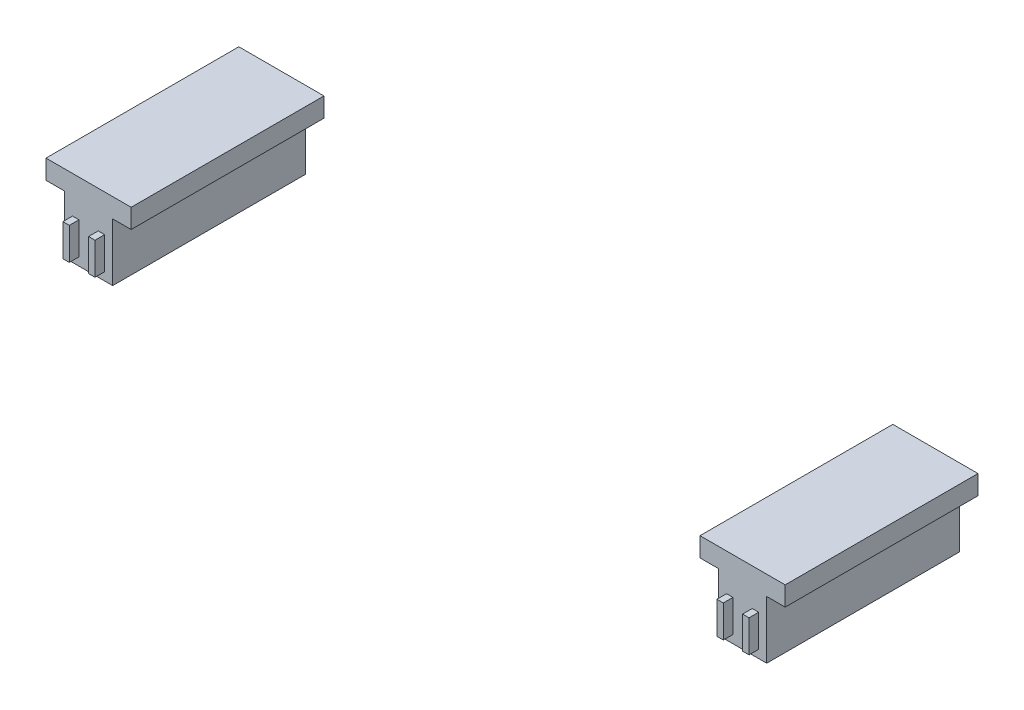
SolidWorks part; units mm, degrees
ref_plane "Front Plane" through (0, 0, 0) normal (0, 0, 1) x (1, 0, 0)
ref_plane "Top Plane" through (0, 0, 0) normal (0, 1, 0) x (1, 0, 0)
ref_plane "Right Plane" through (0, 0, 0) normal (1, 0, 0) x (0, 0, -1)
sketch "Sketch1" plane through (0, 0, 0) normal (0, 0, 1) x (1, 0, 0)
  line L0 (-56.5163, -7.74) -> (-56.5163, -25.74)
  line L1 (146.9837, -25.74) -> (146.9837, -7.74)
  line L2 (146.9837, -7.74) -> (152.7337, -7.74)
  line L3 (152.7337, -7.74) -> (152.7337, -1.74)
  line L4 (152.7337, -1.74) -> (126.2337, -1.74)
  line L5 (126.2337, -1.74) -> (126.2337, -7.74)
  line L6 (126.2337, -7.74) -> (131.9837, -7.74)
  line L7 (131.9837, -7.74) -> (131.9837, -25.74)
  line L8 (-50.7663, -7.74) -> (-56.5163, -7.74)
  line L9 (-50.7663, -1.74) -> (-50.7663, -7.74)
  line L10 (-77.2663, -1.74) -> (-50.7663, -1.74)
  line L11 (-77.2663, -7.74) -> (-77.2663, -1.74)
  line L12 (-71.5163, -7.74) -> (-77.2663, -7.74)
  line L13 (-71.5163, -25.74) -> (-71.5163, -7.74)
  line L14 (146.9837, -25.74) -> (131.9837, -25.74)
  line L15 (-56.5163, -25.74) -> (-71.5163, -25.74)
extrude "Boss-Extrude1" add sketch "Sketch1" along normal blind 60
sketch "Sketch2" plane through (0, 0, 60) normal (0, 0, 1) x (1, 0, 0)
  line L3 (-69.0163, -23.24) -> (-69.0163, -13.24)
  line L4 (-69.0163, -13.24) -> (-67.0163, -13.24)
  line L5 (-67.0163, -13.24) -> (-67.0163, -23.24)
  line L6 (-67.0163, -23.24) -> (-69.0163, -23.24)
  line L8 (-61.0163, -23.24) -> (-61.0163, -13.24)
  line L9 (-61.0163, -13.24) -> (-59.0163, -13.24)
  line L10 (-59.0163, -13.24) -> (-59.0163, -23.24)
  line L11 (-59.0163, -23.24) -> (-61.0163, -23.24)
  line L12 (134.4837, -23.24) -> (134.4837, -13.24)
  line L13 (134.4837, -13.24) -> (136.4837, -13.24)
  line L14 (136.4837, -13.24) -> (136.4837, -23.24)
  line L15 (136.4837, -23.24) -> (134.4837, -23.24)
  line L16 (142.4837, -23.24) -> (142.4837, -13.24)
  line L17 (142.4837, -13.24) -> (144.4837, -13.24)
  line L18 (144.4837, -13.24) -> (144.4837, -23.24)
  line L19 (144.4837, -23.24) -> (142.4837, -23.24)
extrude "Boss-Extrude2" add sketch "Sketch2" along normal blind 3
